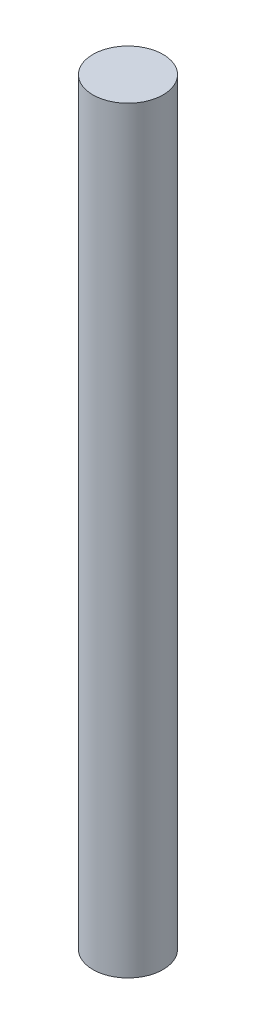
SolidWorks part; units mm, degrees
ref_plane "Front Plane" through (0, 0, 0) normal (0, 0, 1) x (1, 0, 0)
ref_plane "Top Plane" through (0, 0, 0) normal (0, 1, 0) x (1, 0, 0)
ref_plane "Right Plane" through (0, 0, 0) normal (1, 0, 0) x (0, 0, -1)
sketch "Sketch1" plane through (0, 0, 0) normal (0, 1, 0) x (1, 0, 0)
  line L0 (-22.6429, 0) -> (26.1579, 0) construction
  circle A0 centre (0, 0) radius 3.175
  dimension "D1" = 6.35
extrude "Boss-Extrude1" add sketch "Sketch1" along normal blind 68.58
